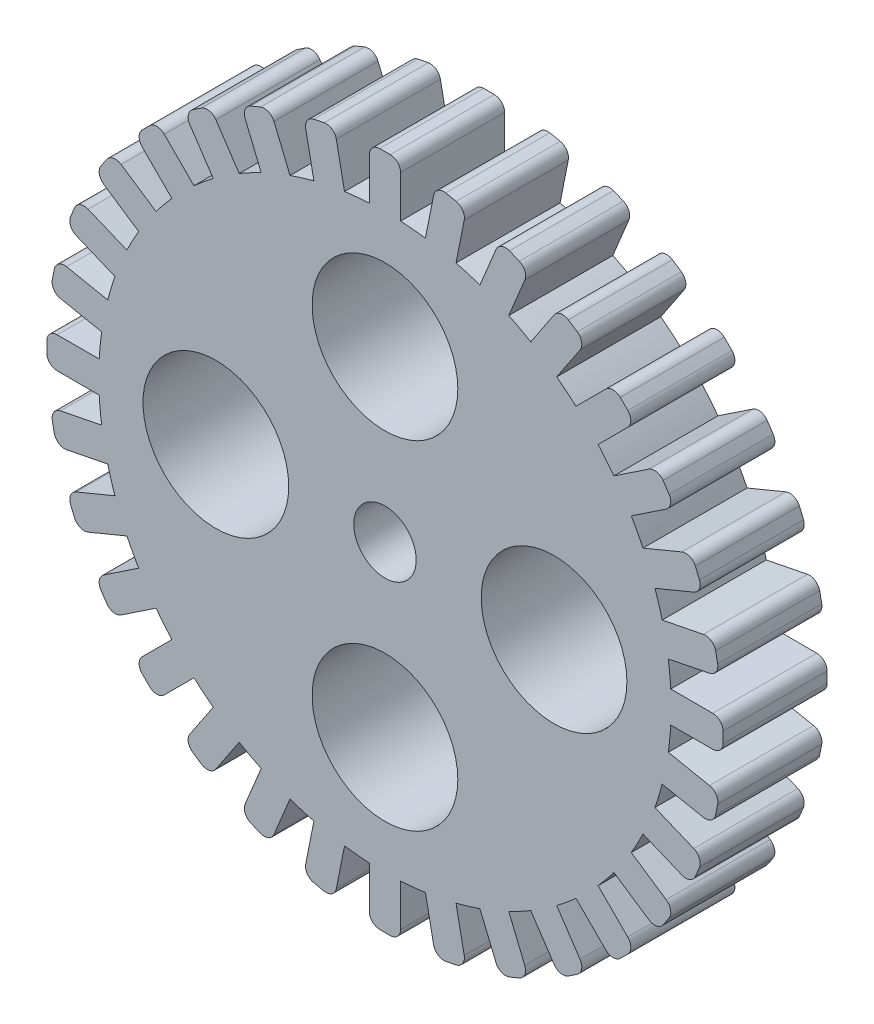
SolidWorks part; units mm, degrees
ref_plane "Front Plane" through (0, 0, 0) normal (0, 0, 1) x (1, 0, 0)
ref_plane "Top Plane" through (0, 0, 0) normal (0, 1, 0) x (1, 0, 0)
ref_plane "Right Plane" through (0, 0, 0) normal (1, 0, 0) x (0, 0, -1)
sketch "Sketch1" plane through (0, 0, 0) normal (0, 0, 1) x (1, 0, 0)
  line L0 (0, 0) -> (0, 3)
  line L1 (4.8625, 32.1342) -> (3.8858, 27.2241)
  line L2 (7.8049, 31.5489) -> (6.8282, 26.6388)
  line L3 (11.0381, 30.5681) -> (9.1223, 25.9429)
  line L4 (13.8098, 29.4201) -> (11.8939, 24.7948)
  line L5 (16.7896, 27.8273) -> (14.0082, 23.6647)
  line L6 (-1.5, 32.4654) -> (-1.5, 27.4591)
  line L7 (1.5, 32.4654) -> (1.5, 27.4591)
  line L8 (19.284, 26.1606) -> (16.5026, 21.998)
  line L9 (21.8958, 24.0171) -> (18.3558, 20.4771)
  line L10 (24.0171, 21.8958) -> (20.4771, 18.3558)
  line L11 (26.1606, 19.284) -> (21.998, 16.5026)
  line L12 (27.8273, 16.7896) -> (23.6647, 14.0082)
  line L13 (29.4201, 13.8098) -> (24.7948, 11.8939)
  line L14 (30.5681, 11.0381) -> (25.9429, 9.1223)
  line L15 (31.5489, 7.8049) -> (26.6388, 6.8282)
  line L16 (32.1342, 4.8625) -> (27.2241, 3.8858)
  line L17 (32.4654, 1.5) -> (27.4591, 1.5)
  line L18 (32.4654, -1.5) -> (27.4591, -1.5)
  line L19 (32.1342, -4.8625) -> (27.2241, -3.8858)
  line L20 (31.5489, -7.8049) -> (26.6388, -6.8282)
  line L21 (30.5681, -11.0381) -> (25.9429, -9.1223)
  line L22 (29.4201, -13.8098) -> (24.7948, -11.8939)
  line L23 (27.8273, -16.7896) -> (23.6647, -14.0082)
  line L24 (26.1606, -19.284) -> (21.998, -16.5026)
  line L25 (24.0171, -21.8958) -> (20.4771, -18.3558)
  line L26 (21.8958, -24.0171) -> (18.3558, -20.4771)
  line L27 (19.284, -26.1606) -> (16.5026, -21.998)
  line L28 (16.7896, -27.8273) -> (14.0082, -23.6647)
  line L29 (13.8098, -29.4201) -> (11.8939, -24.7948)
  line L30 (11.0381, -30.5681) -> (9.1223, -25.9429)
  line L31 (7.8049, -31.5489) -> (6.8282, -26.6388)
  line L32 (4.8625, -32.1342) -> (3.8858, -27.2241)
  line L33 (1.5, -32.4654) -> (1.5, -27.4591)
  line L34 (-1.5, -32.4654) -> (-1.5, -27.4591)
  line L35 (-4.8625, -32.1342) -> (-3.8858, -27.2241)
  line L36 (-7.8049, -31.5489) -> (-6.8282, -26.6388)
  line L37 (-11.0381, -30.5681) -> (-9.1223, -25.9429)
  line L38 (-13.8098, -29.4201) -> (-11.8939, -24.7948)
  line L39 (-16.7896, -27.8273) -> (-14.0082, -23.6647)
  line L40 (-19.284, -26.1606) -> (-16.5026, -21.998)
  line L41 (-21.8958, -24.0171) -> (-18.3558, -20.4771)
  line L42 (-24.0171, -21.8958) -> (-20.4771, -18.3558)
  line L43 (-26.1606, -19.284) -> (-21.998, -16.5026)
  line L44 (-27.8273, -16.7896) -> (-23.6647, -14.0082)
  line L45 (-29.4201, -13.8098) -> (-24.7948, -11.8939)
  line L46 (-30.5681, -11.0381) -> (-25.9429, -9.1223)
  line L47 (-31.5489, -7.8049) -> (-26.6388, -6.8282)
  line L48 (-32.1342, -4.8625) -> (-27.2241, -3.8858)
  line L49 (-32.4654, -1.5) -> (-27.4591, -1.5)
  line L50 (-32.4654, 1.5) -> (-27.4591, 1.5)
  line L51 (-32.1342, 4.8625) -> (-27.2241, 3.8858)
  line L52 (-31.5489, 7.8049) -> (-26.6388, 6.8282)
  line L53 (-30.5681, 11.0381) -> (-25.9429, 9.1223)
  line L54 (-29.4201, 13.8098) -> (-24.7948, 11.8939)
  line L55 (-27.8273, 16.7896) -> (-23.6647, 14.0082)
  line L56 (-26.1606, 19.284) -> (-21.998, 16.5026)
  line L57 (-24.0171, 21.8958) -> (-20.4771, 18.3558)
  line L58 (-21.8958, 24.0171) -> (-18.3558, 20.4771)
  line L59 (-19.284, 26.1606) -> (-16.5026, 21.998)
  line L60 (-16.7896, 27.8273) -> (-14.0082, 23.6647)
  line L61 (-13.8098, 29.4201) -> (-11.8939, 24.7948)
  line L62 (-11.0381, 30.5681) -> (-9.1223, 25.9429)
  line L63 (-7.8049, 31.5489) -> (-6.8282, 26.6388)
  line L64 (-4.8625, 32.1342) -> (-3.8858, 27.2241)
  arc A0 (1.5, 32.4654) -> (-1.5, 32.4654) centre (0, 0) ccw
  arc A1 (-6.8282, 26.6388) -> (-9.1223, 25.9429) centre (0, 0) ccw
  circle A2 centre (0, 0) radius 3
  arc A3 (7.8049, 31.5489) -> (4.8625, 32.1342) centre (0, 0) ccw
  arc A4 (13.8098, 29.4201) -> (11.0381, 30.5681) centre (0, 0) ccw
  arc A5 (19.284, 26.1606) -> (16.7896, 27.8273) centre (0, 0) ccw
  arc A6 (24.0171, 21.8958) -> (21.8958, 24.0171) centre (0, 0) ccw
  arc A7 (27.8273, 16.7896) -> (26.1606, 19.284) centre (0, 0) ccw
  arc A8 (30.5681, 11.0381) -> (29.4201, 13.8098) centre (0, 0) ccw
  arc A9 (32.1342, 4.8625) -> (31.5489, 7.8049) centre (0, 0) ccw
  arc A10 (32.4654, -1.5) -> (32.4654, 1.5) centre (0, 0) ccw
  arc A11 (31.5489, -7.8049) -> (32.1342, -4.8625) centre (0, 0) ccw
  arc A12 (29.4201, -13.8098) -> (30.5681, -11.0381) centre (0, 0) ccw
  arc A13 (26.1606, -19.284) -> (27.8273, -16.7896) centre (0, 0) ccw
  arc A14 (21.8958, -24.0171) -> (24.0171, -21.8958) centre (0, 0) ccw
  arc A15 (16.7896, -27.8273) -> (19.284, -26.1606) centre (0, 0) ccw
  arc A16 (11.0381, -30.5681) -> (13.8098, -29.4201) centre (0, 0) ccw
  arc A17 (4.8625, -32.1342) -> (7.8049, -31.5489) centre (0, 0) ccw
  arc A18 (-1.5, -32.4654) -> (1.5, -32.4654) centre (0, 0) ccw
  arc A19 (-7.8049, -31.5489) -> (-4.8625, -32.1342) centre (0, 0) ccw
  arc A20 (-13.8098, -29.4201) -> (-11.0381, -30.5681) centre (0, 0) ccw
  arc A21 (-19.284, -26.1606) -> (-16.7896, -27.8273) centre (0, 0) ccw
  arc A22 (-24.0171, -21.8958) -> (-21.8958, -24.0171) centre (0, 0) ccw
  arc A23 (-27.8273, -16.7896) -> (-26.1606, -19.284) centre (0, 0) ccw
  arc A24 (-30.5681, -11.0381) -> (-29.4201, -13.8098) centre (0, 0) ccw
  arc A25 (-32.1342, -4.8625) -> (-31.5489, -7.8049) centre (0, 0) ccw
  arc A26 (-32.4654, 1.5) -> (-32.4654, -1.5) centre (0, 0) ccw
  arc A27 (-31.5489, 7.8049) -> (-32.1342, 4.8625) centre (0, 0) ccw
  arc A28 (-29.4201, 13.8098) -> (-30.5681, 11.0381) centre (0, 0) ccw
  arc A29 (-26.1606, 19.284) -> (-27.8273, 16.7896) centre (0, 0) ccw
  arc A30 (-21.8958, 24.0171) -> (-24.0171, 21.8958) centre (0, 0) ccw
  arc A31 (-16.7896, 27.8273) -> (-19.284, 26.1606) centre (0, 0) ccw
  arc A32 (-11.0381, 30.5681) -> (-13.8098, 29.4201) centre (0, 0) ccw
  arc A33 (-4.8625, 32.1342) -> (-7.8049, 31.5489) centre (0, 0) ccw
  arc A34 (-1.5, 27.4591) -> (-3.8858, 27.2241) centre (0, 0) ccw
  arc A35 (3.8858, 27.2241) -> (1.5, 27.4591) centre (0, 0) ccw
  arc A36 (9.1223, 25.9429) -> (6.8282, 26.6388) centre (0, 0) ccw
  arc A37 (14.0082, 23.6647) -> (11.8939, 24.7948) centre (0, 0) ccw
  arc A38 (18.3558, 20.4771) -> (16.5026, 21.998) centre (0, 0) ccw
  arc A39 (21.998, 16.5026) -> (20.4771, 18.3558) centre (0, 0) ccw
  arc A40 (24.7948, 11.8939) -> (23.6647, 14.0082) centre (0, 0) ccw
  arc A41 (26.6388, 6.8282) -> (25.9429, 9.1223) centre (0, 0) ccw
  arc A42 (27.4591, 1.5) -> (27.2241, 3.8858) centre (0, 0) ccw
  arc A43 (27.2241, -3.8858) -> (27.4591, -1.5) centre (0, 0) ccw
  arc A44 (25.9429, -9.1223) -> (26.6388, -6.8282) centre (0, 0) ccw
  arc A45 (-16.5026, 21.998) -> (-18.3558, 20.4771) centre (0, 0) ccw
  arc A46 (-20.4771, 18.3558) -> (-21.998, 16.5026) centre (0, 0) ccw
  arc A47 (-23.6647, 14.0082) -> (-24.7948, 11.8939) centre (0, 0) ccw
  arc A48 (-27.2241, 3.8858) -> (-27.4591, 1.5) centre (0, 0) ccw
  arc A49 (-27.4591, -1.5) -> (-27.2241, -3.8858) centre (0, 0) ccw
  arc A50 (-26.6388, -6.8282) -> (-25.9429, -9.1223) centre (0, 0) ccw
  arc A51 (-24.7948, -11.8939) -> (-23.6647, -14.0082) centre (0, 0) ccw
  arc A52 (-21.998, -16.5026) -> (-20.4771, -18.3558) centre (0, 0) ccw
  arc A53 (-18.3558, -20.4771) -> (-16.5026, -21.998) centre (0, 0) ccw
  arc A54 (-14.0082, -23.6647) -> (-11.8939, -24.7948) centre (0, 0) ccw
  arc A55 (-9.1223, -25.9429) -> (-6.8282, -26.6388) centre (0, 0) ccw
  arc A56 (-3.8858, -27.2241) -> (-1.5, -27.4591) centre (0, 0) ccw
  arc A57 (1.5, -27.4591) -> (3.8858, -27.2241) centre (0, 0) ccw
  arc A58 (6.8282, -26.6388) -> (9.1223, -25.9429) centre (0, 0) ccw
  arc A59 (11.8939, -24.7948) -> (14.0082, -23.6647) centre (0, 0) ccw
  arc A60 (16.5026, -21.998) -> (18.3558, -20.4771) centre (0, 0) ccw
  arc A61 (20.4771, -18.3558) -> (21.998, -16.5026) centre (0, 0) ccw
  arc A62 (-25.9429, 9.1223) -> (-26.6388, 6.8282) centre (0, 0) ccw
  arc A63 (-11.8939, 24.7948) -> (-14.0082, 23.6647) centre (0, 0) ccw
  arc A64 (23.6647, -14.0082) -> (24.7948, -11.8939) centre (0, 0) ccw
  dimension "D1" = 32
extrude "Boss-Extrude2" add sketch "Sketch1" along normal blind 10 contours L23 A64 L22 A12 L21 A44 L20 A11 L19 A43 L18 A10 L17 A42 L16 A9 L15 A41 L14 A8 L13 A40 L12 A7 L11 A39 L10 A6 L9 A38 L8 A5 L5 A37 L4 A4 L3 A36 L2 A3 L1 A35 L7 A0 L6 A34 L64 A33 L63 A1 L62
fillet "Fillet1" radius 1 64 edges at (29.4201, 13.8098, 5) (30.5681, 11.0381, 5) (31.5489, 7.8049, 5) (32.1342, 4.8625, 5) (32.4654, 1.5, 5) (32.4654, -1.5, 5) (32.1342, -4.8625, 5) (31.5489, -7.8049, 5) (30.5681, -11.0381, 5) (29.4201, -13.8098, 5) (27.8273, -16.7896, 5) (26.1606, -19.284, 5) (24.0171, -21.8958, 5) (21.8958, -24.0171, 5) (19.284, -26.1606, 5) (16.7896, -27.8273, 5) (13.8098, -29.4201, 5) (11.0381, -30.5681, 5) (7.8049, -31.5489, 5) (4.8625, -32.1342, 5) (1.5, -32.4654, 5) (-1.5, -32.4654, 5) (-4.8625, -32.1342, 5) (-7.8049, -31.5489, 5) (-11.0381, -30.5681, 5) (-13.8098, -29.4201, 5) (-16.7896, -27.8273, 5) (-19.284, -26.1606, 5) (-21.8958, -24.0171, 5) (-24.0171, -21.8958, 5) (-26.1606, -19.284, 5) (-27.8273, -16.7896, 5) (-29.4201, -13.8098, 5) (-30.5681, -11.0381, 5) (-31.5489, -7.8049, 5) (-32.1342, -4.8625, 5) (-32.4654, -1.5, 5) (-32.4654, 1.5, 5) (-32.1342, 4.8625, 5) (-31.5489, 7.8049, 5) (-30.5681, 11.0381, 5) (-29.4201, 13.8098, 5) (-27.8273, 16.7896, 5) (-26.1606, 19.284, 5) (-24.0171, 21.8958, 5) (-21.8958, 24.0171, 5) (-19.284, 26.1606, 5) (-16.7896, 27.8273, 5) (-13.8098, 29.4201, 5) (-11.0381, 30.5681, 5) (-7.8049, 31.5489, 5) (-4.8625, 32.1342, 5) (-1.5, 32.4654, 5) (1.5, 32.4654, 5) (4.8625, 32.1342, 5) (7.8049, 31.5489, 5) (11.0381, 30.5681, 5) (13.8098, 29.4201, 5) (16.7896, 27.8273, 5) (19.284, 26.1606, 5) (21.8958, 24.0171, 5) (24.0171, 21.8958, 5) (26.1606, 19.284, 5) (27.8273, 16.7896, 5)
sketch "Sketch2" plane through (0, 0, 0) normal (0, 0, 1) x (1, 0, 0)
  line L0 (0, 0) -> (32.5, 0)
  arc A0 (32.4959, -0.5159) -> (32.4959, 0.5159) centre (0, 0) ccw construction
  circle A1 centre (16.25, 0) radius 7
  circle A2 centre (0, -16.25) radius 7
  circle A3 centre (-16.25, 0) radius 7
  circle A4 centre (0, 16.25) radius 7
  dimension "D1" = 14
  dimension "D2" = 4
extrude "Cut-Extrude1" cut sketch "Sketch2" along normal blind 24 contours A3 | A2 | A4 | L0 A1 | L0 A1
